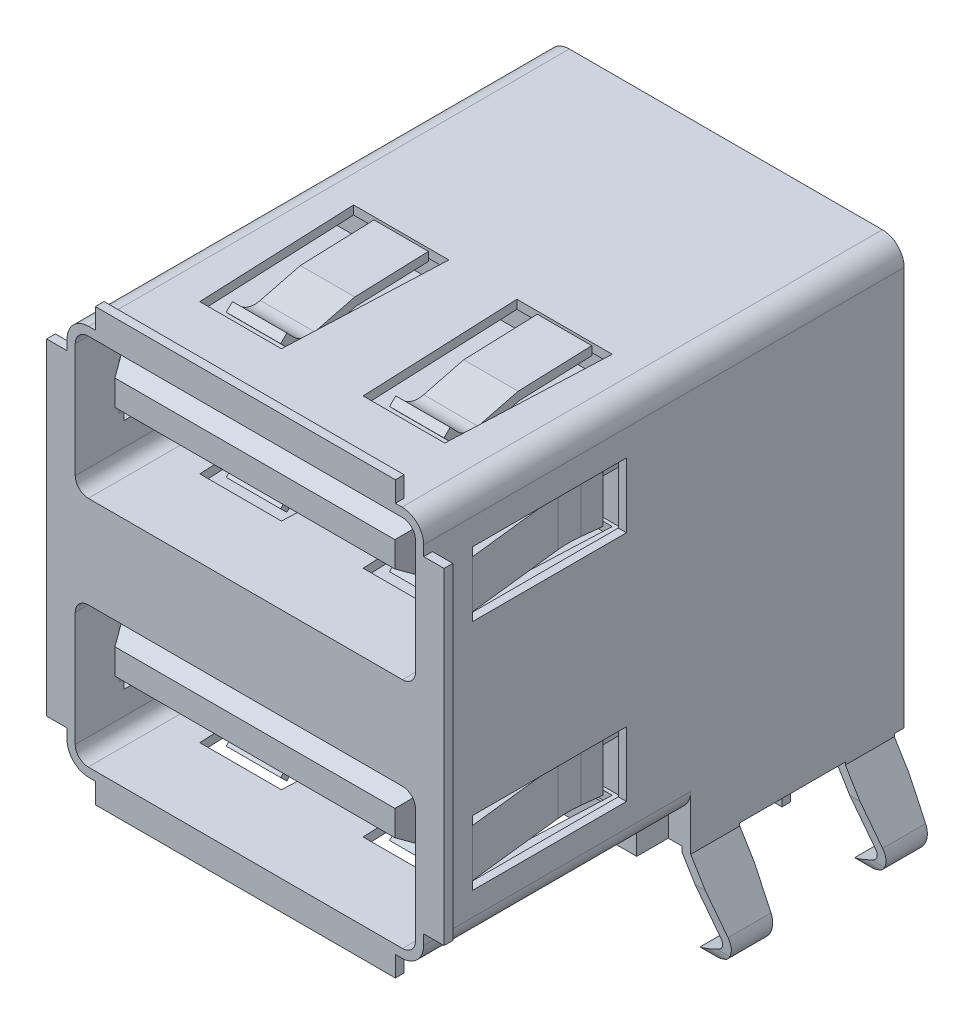
SolidWorks part; units mm, degrees
ref_plane "Front" through (0, 0, 0) normal (0, 0, 1) x (1, 0, 0)
ref_plane "Top" through (0, 0, 0) normal (0, 1, 0) x (1, 0, 0)
ref_plane "Side" through (0, 0, 0) normal (1, 0, 0) x (0, 0, -1)
ref_plane "Position 1 Plane" through (-3.5, 0, 0) normal (1, 0, 0) x (0, 0, -1)
sketch "Sketch1" plane through (0, 0, 0) normal (0, 1, 0) x (1, 0, 0)
  line L0 (6.55, -8.825) -> (-6.55, 8.825) construction
  line L1 (-6.55, 8.825) -> (6.55, 8.825)
  line L2 (-6.55, 8.825) -> (-6.55, -8.825)
  line L3 (-6.55, -8.825) -> (6.55, -8.825)
  line L4 (6.55, 8.825) -> (6.55, -8.825)
  dimension "D1" = 13.1
  dimension "D2" = 17.65
extrude "Base" add sketch "Sketch1" along normal blind 14.35
ref_plane "Ground Tail Plane" through (0, 0, -1.885) normal (0, 0, 1) x (1, 0, 0)
ref_plane "Top/Bottom Flange Plane" through (-3, 0, 0) normal (1, 0, 0) x (0, 0, -1)
ref_plane "Mid Plane" through (0, 2.85, 0) normal (0, 1, 0) x (-1, 0, 0)
ref_plane "Back Plane" through (0, 0, -8.825) normal (0, 0, 1) x (1, 0, 0)
ref_plane "Cut Plane" through (0, 0, -0.075) normal (0, 0, 1) x (1, 0, 0)
sketch "Sketch3" plane through (0, 0, 8.825) normal (0, 0, 1) x (1, 0, 0)
  line L0 (-6.55, 14.35) -> (6.55, 14.35) construction
  line L1 (-5.51, 14.35) -> (5.51, 14.35)
  line L2 (-5.51, 14.35) -> (-5.51, 15.1)
  line L3 (-5.51, 15.1) -> (5.51, 15.1)
  line L4 (5.51, 14.35) -> (5.51, 15.1)
  line L5 (6.55, 14.35) -> (6.55, 0) construction
  line L6 (6.55, 13.175) -> (7.3, 13.175)
  line L7 (6.55, 13.175) -> (6.55, 1.175)
  line L8 (6.55, 1.175) -> (7.3, 1.175)
  line L9 (7.3, 13.175) -> (7.3, 1.175)
  line L10 (0, 15.1) -> (0, 14.35) construction
  line L11 (6.55, 7.175) -> (7.3, 7.175) construction
  line L12 (-6.55, 14.35) -> (6.55, 0) construction
  line L13 (0, 7.175) -> (3.5942, 7.175) construction
  line L14 (5.51, 0) -> (5.51, -0.75)
  line L15 (-5.51, -0.75) -> (5.51, -0.75)
  line L16 (-5.51, 0) -> (-5.51, -0.75)
  line L17 (-5.51, 0) -> (5.51, 0)
  line L18 (0, 7.175) -> (0, 4.7958) construction
  line L19 (-7.3, 13.175) -> (-7.3, 1.175)
  line L20 (-6.55, 1.175) -> (-7.3, 1.175)
  line L21 (-6.55, 13.175) -> (-6.55, 1.175)
  line L22 (-6.55, 13.175) -> (-7.3, 13.175)
  dimension "D1" = 14.6
  dimension "D2" = 11.02
  dimension "D3" = 15.85
  dimension "D4" = 12
extrude "Front Tabs" add sketch "Sketch3" against normal blind 0.32
fillet "Corner Fillets" radius 0.8 4 edges at (-6.55, 14.35, 0) (-6.55, 0, 0) (6.55, 0, 0) (6.55, 14.35, 0)
sketch "Sketch18" plane through (0, 0, -8.825) normal (0, 0, -1) x (-1, 0, 0)
  line L0 (-6.55, 0.8) -> (-6.55, -1.1)
  line L1 (-6.55, -1.1) -> (6.55, -1.1)
  line L2 (6.55, -1.1) -> (6.55, 0.8)
  line L3 (-5.75, 0) -> (5.75, 0) construction
  line L4 (-5.75, 0) -> (5.75, 0)
  line L5 (0, 0) -> (0, -1.6279) construction
  arc A2 (-6.55, 0.8) -> (-5.75, 0) centre (-5.75, 0.8) ccw
  arc A3 (5.75, 0) -> (6.55, 0.8) centre (5.75, 0.8) ccw
  point P13 (0, -1.1)
  dimension "D2" = 0.8
  dimension "D1" = 1.1
extrude "-D Back Step" add sketch "Sketch18" against normal blind 7.84
sketch "Sketch19" plane through (0, 0, 0) normal (0, -1, 0) x (1, 0, 0)
  line L0 (6.55, -0.985) -> (-6.55, -0.985) construction
  line L1 (5.725, -0.985) -> (-5.725, -0.985)
  line L2 (5.725, -0.985) -> (5.725, 0.175)
  line L3 (5.725, 0.175) -> (-5.725, 0.175)
  line L4 (-5.725, -0.985) -> (-5.725, 0.175)
  line L5 (0, 0.175) -> (0, -0.985) construction
  line L6 (6.55, -8.825) -> (-6.55, -8.825) construction
  dimension "D1" = 9
  dimension "D2" = 11.45
extrude "-D Bottom Step" add sketch "Sketch19" along normal up to surface (1.1 mm away) up to face at (0, -1.1, -4.905)
sketch "Sketch10" plane through (0, 0, -1.885) normal (0, 0, 1) x (1, 0, 0)
  line L0 (6.55, -1.2) -> (6.55, -1.1)
  line L2 (6.55, -1.2) -> (7.8102, -3.2786)
  line L3 (7.5651, -4.1506) -> (6.6971, -4.6)
  line L4 (7.5365, -3.4445) -> (6.23, -1.2894)
  line L5 (-5.75, 0) -> (-5.51, 0) construction
  line L6 (5.725, 0) -> (-5.725, 0) construction
  line L7 (6.55, 1.175) -> (6.55, 0.8) construction
  line L8 (6.23, -1.1) -> (6.23, -1.2894)
  line L9 (7.4179, -3.8664) -> (6.55, -4.3158)
  line L10 (6.55, -4.3158) -> (6.6971, -4.6)
  line L11 (6.23, -1.1) -> (6.23, -1.2071) construction
  line L12 (6.55, -1.1) -> (6.23, -1.1)
  line L13 (0, 0) -> (0, -2.9377) construction
  line L14 (6.3579, -1.5004) -> (7.5365, -3.4445) construction
  line L15 (-6.55, -1.1) -> (-6.23, -1.1)
  line L16 (-6.55, -4.3158) -> (-6.6971, -4.6)
  line L17 (-7.4179, -3.8664) -> (-6.55, -4.3158)
  line L18 (-6.23, -1.1) -> (-6.23, -1.2894)
  line L19 (-6.23, -1.2894) -> (-7.5365, -3.4445)
  line L20 (-7.5651, -4.1506) -> (-6.6971, -4.6)
  line L21 (-6.55, -1.2) -> (-7.8102, -3.2786)
  line L22 (-6.55, -1.2) -> (-6.55, -1.1)
  line L24 (6.3579, -1.5004) -> (6.3579, -1.5004) construction
  line L25 (6.3579, -1.5004) -> (6.3579, -1.5004) construction
  line L26 (6.3579, -1.5004) -> (6.3579, -1.5004) construction
  arc A0 (7.8102, -3.2786) -> (7.5651, -4.1506) centre (7.28, -3.6) cw
  arc A1 (7.5365, -3.4445) -> (7.4179, -3.8664) centre (7.28, -3.6) cw
  arc A2 (-7.5365, -3.4445) -> (-7.4179, -3.8664) centre (-7.28, -3.6) ccw
  arc A3 (-7.8102, -3.2786) -> (-7.5651, -4.1506) centre (-7.28, -3.6) ccw
  arc A4 (7.8102, -3.2786) -> (7.5651, -4.1506) centre (7.28, -3.6) cw construction
  dimension "D2" = 0.32
  dimension "D5" = 0.3
  dimension "D7" = 15.8
  dimension "D6" = 3.6
  dimension "D1" = 13.1
  dimension "D3" = 4.6
  dimension "D4" = 0.1
  dimension "D8" = 0.32
  dimension "D9" = 1.1
extrude "Ground Tail 1" add sketch "Sketch10" along normal mid plane 1.8
sketch "Sketch11" plane through (0, 0, 0) normal (1, 0, 0) x (0, 0, -1)
  line L0 (0.96, -1.8091) -> (1.1533, -3.9065)
  line L1 (1.885, 7.92) -> (1.885, -7.92) construction
  line L3 (2.81, -1.8091) -> (2.6167, -3.9065)
  line L4 (0.96, -1.8091) -> (0.96, -4.9391)
  line L6 (0.96, -4.9391) -> (2.81, -4.9391)
  line L7 (2.81, -4.9391) -> (2.81, -1.8091)
  line L8 (1.885, -4.85) -> (1.885, -6.7183) construction
  arc A0 (1.1533, -3.9065) -> (2.6167, -3.9065) centre (1.885, -3.8391) ccw
  point P5 (1.885, -4.9391)
  dimension "D2" = 0.7348
  dimension "D1" = 1.85
  dimension "D3" = 1.1
  dimension "D4" = 4.9391
  dimension "D5" = 2.0974
extrude "Ground Tail 1 Shape" cut sketch "Sketch11" against normal mid plane 16
pattern_linear "Ground Tail Pattern" count 2 spacing 5.68 along (0, 0, -1) of "Ground Tail 1", "Ground Tail 1 Shape"
sketch "Sketch23" plane through (0, 0, 0) normal (0, -1, 0) x (1, 0, 0)
  line L0 (-3.5098, -4.4478) -> (-3.5098, -4.7578) construction
  line L1 (-3.1796, -4.4478) -> (-3.84, -4.4478)
  line L2 (-3.1796, -4.4478) -> (-3.1796, -4.7578)
  line L3 (-3.1796, -4.7578) -> (-3.84, -4.7578)
  line L4 (-3.84, -4.4478) -> (-3.84, -4.7578)
  line L5 (-3.1796, -4.6028) -> (-3.84, -4.6028) construction
  line L6 (3.16, -4.4478) -> (3.16, -4.7578)
  line L7 (3.8204, -4.4478) -> (3.16, -4.4478)
  line L8 (3.8204, -4.4478) -> (3.8204, -4.7578)
  line L9 (3.8204, -4.7578) -> (3.16, -4.7578)
  line L10 (-1.34, -4.4478) -> (-1.34, -4.7578)
  line L11 (-0.6796, -4.4478) -> (-1.34, -4.4478)
  line L12 (-0.6796, -4.4478) -> (-0.6796, -4.7578)
  line L13 (-0.6796, -4.7578) -> (-1.34, -4.7578)
  line L14 (0.66, -4.4478) -> (0.66, -4.7578)
  line L15 (1.3204, -4.4478) -> (0.66, -4.4478)
  line L16 (1.3204, -4.4478) -> (1.3204, -4.7578)
  line L17 (1.3204, -4.7578) -> (0.66, -4.7578)
  line L18 (0, 0) -> (0, -8.093) construction
  line L19 (7.92, -1.885) -> (-7.92, -1.885) construction
  dimension "D1" = 2.5
  dimension "D2" = 2
  dimension "D3" = 2.5
  dimension "D4" = 0.31
  dimension "D5" = 1.34
  dimension "D6" = 0.6604
  dimension "D7" = 2.7178
extrude "-TH Contact Tail" add sketch "Sketch23" along normal blind 4.1
pattern_linear "-TH Contact Pattern" count 2 spacing 2.62 along (0, 0, -1) of "-TH Contact Tail"
sketch "Sketch8" plane through (0, 0, 8.825) normal (0, 0, 1) x (1, 0, 0)
  line L0 (-6.25, 5) -> (-6.25, 0.8)
  line L1 (-5.77, 0.32) -> (5.77, 0.32)
  line L2 (-5.77, 5.48) -> (5.77, 5.48)
  line L3 (6.25, 0.8) -> (6.25, 5)
  line L4 (0, 0) -> (0, 6.7662) construction
  arc A16 (6.25, 5) -> (5.77, 5.48) centre (5.77, 5) ccw
  arc A17 (5.77, 0.32) -> (6.25, 0.8) centre (5.77, 0.8) ccw
  arc A18 (-6.25, 0.8) -> (-5.77, 0.32) centre (-5.77, 0.8) ccw
  arc A19 (-5.77, 5.48) -> (-6.25, 5) centre (-5.77, 5) ccw
  point P4 (0, 5.48)
  dimension "D2" = 0.48
  dimension "D1" = 12.5
  dimension "D3" = 0.32
  dimension "D4" = 5.16
extrude "Contact Area Cutout" cut sketch "Sketch8" against normal blind 8.85
sketch "Sketch12" plane through (0, 0, 0) normal (0, 1, 0) x (-1, 0, 0)
  line L0 (0, 0) -> (0, 5.7946) construction
  line L1 (4.5, 6) -> (4.75, 0.1)
  line L2 (3, 4.5748) -> (3, 0.3752) construction
  line L3 (1.5, 6) -> (1.25, 0.1)
  line L4 (4.5, 6) -> (1.5, 6)
  line L5 (4.75, 0.1) -> (1.25, 0.1)
  line L7 (-4.75, 0.1) -> (-1.25, 0.1)
  line L8 (-4.5, 6) -> (-1.5, 6)
  line L9 (-1.5, 6) -> (-1.25, 0.1)
  line L10 (-4.5, 6) -> (-4.75, 0.1)
  dimension "D1" = 3.5
  dimension "D2" = 3
  dimension "D3" = 5.9
  dimension "D4" = 6
  dimension "D5" = 3
extrude "Top/Bottom Flange Cutout" cut sketch "Sketch12" along normal blind 5.8
sketch "Sketch13" plane through (-3, 0, 0) normal (1, 0, 0) x (0, 0, -1)
  line L0 (-2.7601, 0.4175) -> (-4.1983, 0.7842)
  line L1 (7.05, 2.85) -> (-8.6639, 2.85) construction
  line L2 (-2.8059, 5.6011) -> (-4.2773, 5.2259)
  line L3 (-5.0476, 5.4424) -> (-5.3, 5.7011)
  line L4 (-5.2766, 5.2189) -> (-5.529, 5.4776)
  line L5 (-2.7601, 5.2825) -> (-4.1983, 4.9158)
  line L6 (-2.8059, 5.6011) -> (-0.1, 5.699)
  line L7 (-5.529, 5.4776) -> (-5.3, 5.7011)
  line L8 (-0.1, 5.699) -> (-0.1, 5.3788)
  line L9 (0.985, 0) -> (-8.825, 0) construction
  line L10 (-5.3, 5.7011) -> (-5.3, -0.0011) construction
  line L12 (-2.7601, 0.4175) -> (-0.1, 0.3212)
  line L13 (-0.1, 0.001) -> (-0.1, 0.3212)
  line L14 (-5.529, 0.2224) -> (-5.3, -0.0011)
  line L15 (-2.8059, 0.0989) -> (-0.1, 0.001)
  line L16 (-5.2766, 0.4811) -> (-5.529, 0.2224)
  line L17 (-2.7601, 5.2825) -> (-0.1, 5.3788)
  line L18 (-5.0476, 0.2576) -> (-5.3, -0.0011)
  line L19 (-2.8059, 0.0989) -> (-4.2773, 0.4741)
  line L20 (0.6313, 2.85) -> (-0.6313, 2.85) construction
  arc A0 (-4.2773, 5.2259) -> (-5.0476, 5.4424) centre (-4.475, 6.0011) cw
  arc A1 (-4.1983, 4.9158) -> (-5.2766, 5.2189) centre (-4.475, 6.0011) cw
  arc A2 (-4.1983, 0.7842) -> (-5.2766, 0.4811) centre (-4.475, -0.3011) ccw
  arc A3 (-4.2773, 0.4741) -> (-5.0476, 0.2576) centre (-4.475, -0.3011) ccw
  point P15 (-5.3, 2.85)
  dimension "D3" = 0.8
  dimension "D6" = 5.2
  dimension "D8" = 0.4
  dimension "D2" = 4.375
  dimension "D4" = 2.7059
  dimension "D5" = 0.32
  dimension "D7" = 0.3614
  dimension "D9" = 0.32
  dimension "D10" = 5.7021
  dimension "D11" = 0.1
  dimension "D13" = 0.001
extrude "Top/Bottom Flange" add sketch "Sketch13" along normal mid plane 2
pattern_linear "Top/Bottom Flange Pattern" count 2 spacing 6 along (1, 0, 0) of "Top/Bottom Flange"
sketch "Sketch14" plane through (6.55, 0, 0) normal (1, 0, 0) x (0, 0, -1)
  line L0 (0.6313, 2.85) -> (-0.6313, 2.85) construction
  line L1 (-7.025, 4.04) -> (-1.375, 4.04)
  line L2 (-7.025, 4.04) -> (-7.025, 1.66)
  line L3 (-7.025, 1.66) -> (-1.375, 1.66)
  line L4 (-1.375, 4.04) -> (-1.375, 1.66)
  line L7 (7.05, 2.85) -> (-7.9068, 2.85) construction
  line L8 (-8.825, 1.175) -> (-8.825, 0.8) construction
  point P4 (-7.025, 2.85)
  dimension "D1" = 2.38
  dimension "D2" = 5.65
  dimension "D3" = 1.8
extrude "Side Flange Cutout" cut sketch "Sketch14" against normal through all
sketch "Sketch15" plane through (0, 2.85, 0) normal (0, 1, 0) x (-1, 0, 0)
  line L0 (6.55, 7.025) -> (6.149, 3.4987)
  line L1 (6.1488, 2.6528) -> (6.2313, 1.925)
  line L2 (6.55, 7.025) -> (6.25, 7.025) construction
  line L3 (6.55, 8.825) -> (6.55, -8.825) construction
  line L4 (5.8309, 2.6168) -> (5.9133, 1.889)
  line L5 (6.25, 7.219) -> (5.8311, 3.5348)
  line L6 (6.25, 7.219) -> (6.55, 7.025)
  line L7 (5.9133, 1.889) -> (6.2313, 1.925)
  line L8 (0, 0) -> (0, 6.0458) construction
  line L9 (-5.9133, 1.889) -> (-6.2313, 1.925)
  line L10 (-6.25, 7.219) -> (-6.55, 7.025)
  line L11 (-6.25, 7.219) -> (-5.8311, 3.5348)
  line L12 (-5.8309, 2.6168) -> (-5.9133, 1.889)
  line L13 (-6.1488, 2.6528) -> (-6.2313, 1.925)
  line L14 (-6.55, 7.025) -> (-6.149, 3.4987)
  line L15 (6.25, -0.025) -> (6.25, 8.825) construction
  arc A0 (6.149, 3.4987) -> (6.1488, 2.6528) centre (9.875, 3.075) ccw
  arc A1 (5.8311, 3.5348) -> (5.8309, 2.6168) centre (9.875, 3.075) ccw
  arc A2 (-5.8311, 3.5348) -> (-5.8309, 2.6168) centre (-9.875, 3.075) cw
  arc A3 (-6.149, 3.4987) -> (-6.1488, 2.6528) centre (-9.875, 3.075) cw
  dimension "D2" = 3.75
  dimension "D3" = 3.95
  dimension "D4" = 3.325
  dimension "D6" = 3.6437
  dimension "D1" = 5.1
  dimension "D5" = 0.32
extrude "Side Flange" add sketch "Sketch15" along normal mid plane 1.75
sketch "Sketch16" plane through (0, 0, -0.025) normal (0, 0, 1) x (1, 0, 0)
  line L0 (0, 4.72) -> (0, 2.92) construction
  line L1 (-5.575, 4.72) -> (5.575, 4.72)
  line L2 (-5.575, 4.72) -> (-5.575, 2.92)
  line L3 (-5.575, 2.92) -> (5.575, 2.92)
  line L4 (5.575, 4.72) -> (5.575, 2.92)
  line L6 (5.77, 5.48) -> (-5.77, 5.48) construction
  dimension "D1" = 2.56
  dimension "D3" = 1.8
  dimension "D4" = 11.15
extrude "Contact Guide" add sketch "Sketch16" along normal blind 8.5
chamfer "Contact Guide Lead-in" distance 0.75 angle 30 4 edges at (0, 2.92, 8.475) (-5.575, 3.82, 8.475) (0, 4.72, 8.475) (5.575, 3.82, 8.475)
sketch "Sketch17" plane through (-3.5, 0, 0) normal (1, 0, 0) x (0, 0, -1)
  line L0 (0.025, 3.91) -> (0.025, 3.65)
  line L1 (0.025, 4.72) -> (0.025, 2.92) construction
  line L2 (0.025, 3.65) -> (-1.225, 3.65)
  line L3 (-1.225, 3.65) -> (-4.7879, 2.5075)
  line L4 (-6.6912, 2.7571) -> (-7.225, 3.1)
  line L9 (0.025, 0.8) -> (0.025, 5) construction
  line L10 (-6.5507, 2.9758) -> (-7.0845, 3.3187)
  line L11 (-1.2657, 3.91) -> (-4.8673, 2.755)
  line L12 (0.025, 3.91) -> (-1.2657, 3.91)
  line L13 (-7.725, 2.92) -> (0.025, 2.92) construction
  line L15 (-7.225, 3.1) -> (-7.0845, 3.3187)
  arc A0 (-4.7879, 2.5075) -> (-6.6912, 2.7571) centre (-5.475, 4.65) cw
  arc A1 (-4.8673, 2.755) -> (-6.5507, 2.9758) centre (-5.475, 4.65) cw
  dimension "D5" = 2.25
  dimension "D6" = 1
  dimension "D7" = 4.25
  dimension "D2" = 0.73
  dimension "D4" = 1.25
  dimension "D8" = 0.55
  dimension "D9" = 6
  dimension "D10" = 0.26
extrude "Contact" add sketch "Sketch17" along normal mid plane 0.66
pattern_linear "Contact Pattern" count 2 spacing 2.5 along (1, 0, 0) of "Contact"
mirror "Contact Pattern Mirror" about plane through (0, 0, 0) normal (1, 0, 0) of "Contact", "Contact Pattern"
pattern_linear "Top USB Pattern" count 2 spacing 8.55 along (0, 1, 0) of "Contact Area Cutout", "Top/Bottom Flange Cutout", "Top/Bottom Flange", "Top/Bottom Flange Pattern", "Side Flange Cutout", "Side Flange", "Contact Guide", "Contact Guide Lead-in", "Contact", "Contact Pattern", "Contact Pattern Mirror"
sketch "Sketch25" plane through (0, 0, 0.175) normal (0, 0, 1) x (1, 0, 0)
  line L0 (-6.7816, 0) -> (7.0915, 0)
extrude "Cut-Extrude1" [suppressed] cut sketch "Sketch25" against normal through all and the other way through all flip side to cut
sketch "Sketch26" plane through (0, 0, 8.825) normal (0, 0, 1) x (1, 0, 0)
  line L0 (-6.55, 13.175) -> (-6.55, 1.175)
  line L1 (-5.75, 0) -> (5.75, 0)
  line L2 (6.55, 1.175) -> (6.55, 13.175)
  line L3 (7.3, 13.175) -> (6.55, 13.175) construction
  line L4 (-5.51, 14.35) -> (5.51, 14.35)
  line L5 (5.51, 14.35) -> (5.75, 14.35) construction
  line L6 (6.55, 13.55) -> (6.55, 13.175) construction
  line L7 (5.51, 14.35) -> (5.75, 14.35)
  line L8 (6.55, 13.55) -> (6.55, 13.175)
  line L9 (6.55, 1.175) -> (6.55, 0.8) construction
  line L14 (-6.55, 1.175) -> (-6.55, 0.8) construction
  line L15 (-6.55, 13.55) -> (-6.55, 13.175) construction
  line L16 (-5.75, 14.35) -> (-5.51, 14.35) construction
  line L17 (6.55, 1.175) -> (6.55, 0.8)
  line L22 (-6.55, 1.175) -> (-6.55, 0.8)
  line L23 (-6.55, 13.55) -> (-6.55, 13.175)
  line L24 (-5.75, 14.35) -> (-5.51, 14.35)
  arc A0 (6.55, 13.55) -> (5.75, 14.35) centre (5.75, 13.55) ccw construction
  arc A1 (6.55, 13.55) -> (5.75, 14.35) centre (5.75, 13.55) ccw
  arc A2 (5.75, 0) -> (6.55, 0.8) centre (5.75, 0.8) ccw construction
  arc A3 (-6.55, 0.8) -> (-5.75, 0) centre (-5.75, 0.8) ccw construction
  arc A4 (-5.75, 14.35) -> (-6.55, 13.55) centre (-5.75, 13.55) ccw construction
  arc A5 (5.75, 0) -> (6.55, 0.8) centre (5.75, 0.8) ccw
  arc A6 (-6.55, 0.8) -> (-5.75, 0) centre (-5.75, 0.8) ccw
  arc A7 (-5.75, 14.35) -> (-6.55, 13.55) centre (-5.75, 13.55) ccw
extrude "Cut-Extrude2" [suppressed] cut sketch "Sketch26" against normal blind 10 flip side to cut
sketch "Sketch27" [suppressed] plane through (0, 0, 8.825) normal (0, 0, 1) x (1, 0, 0)
  line L0 (-6.55, 0.8) -> (-6.55, 0) construction
  line L1 (-6.55, 0) -> (-5.75, 0) construction
  line L2 (-6.55, 0.8) -> (-6.55, 0)
  line L3 (-6.55, 0) -> (-5.75, 0)
  line L6 (5.75, 0) -> (6.55, 0)
  line L7 (6.55, 0) -> (6.55, 0.8)
  line L8 (5.75, 0) -> (6.55, 0)
  line L9 (6.55, 0) -> (6.55, 0.8)
  arc A0 (-6.55, 0.8) -> (-5.75, 0) centre (-5.75, 0.8) ccw construction
  arc A1 (-6.55, 0.8) -> (-5.75, 0) centre (-5.75, 0.8) ccw
  arc A3 (5.75, 0) -> (6.55, 0.8) centre (5.75, 0.8) ccw
  arc A4 (5.75, 0) -> (6.55, 0.8) centre (5.75, 0.8) ccw
  dimension "D1" = 0
extrude "Cut-Extrude3" [suppressed] cut sketch "Sketch27" against normal through all
